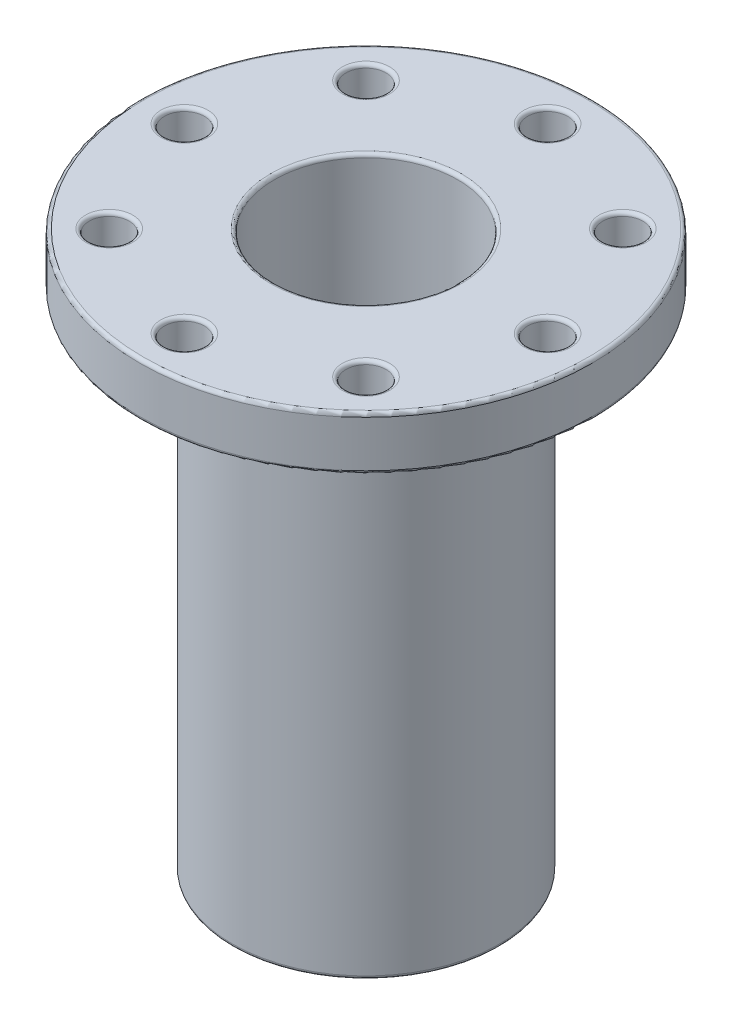
SolidWorks part; units mm, degrees
ref_plane "Front Plane" through (0, 0, 0) normal (0, 0, 1) x (1, 0, 0)
ref_plane "Top Plane" through (0, 0, 0) normal (0, 1, 0) x (1, 0, 0)
ref_plane "Right Plane" through (0, 0, 0) normal (1, 0, 0) x (0, 0, -1)
sketch "Sketch1" plane through (0, 0, 0) normal (0, 1, 0) x (1, 0, 0)
  line L0 (0, 0) -> (0, 20.4) construction
  circle A0 centre (0, 0) radius 25.4
  circle A1 centre (0, 20.4) radius 2.25
  circle A2 centre (14.425, 14.425) radius 2.25
  circle A3 centre (20.4, 0) radius 2.25
  circle A4 centre (14.425, -14.425) radius 2.25
  circle A5 centre (0, -20.4) radius 2.25
  circle A6 centre (-14.425, -14.425) radius 2.25
  circle A7 centre (-20.4, 0) radius 2.25
  circle A8 centre (-14.425, 14.425) radius 2.25
  point P22 (0, 0)
  dimension "D1" = 50.8
  dimension "D2" = 4.5
  dimension "D3" = 20.4
  dimension "D4" = 8
extrude "Boss-Extrude1" add sketch "Sketch1" along normal blind 6
sketch "Sketch2" plane through (0, 6, 0) normal (0, 1, 0) x (1, 0, 0)
  circle A0 centre (0, 0) radius 15
  dimension "D1" = 30
extrude "Boss-Extrude2" add sketch "Sketch2" against normal blind 62.5
sketch "Sketch3" plane through (0, 6, 0) normal (0, 1, 0) x (1, 0, 0)
  circle A0 centre (0, 0) radius 10.3125
  dimension "D1" = 20.625
extrude "Cut-Extrude1" cut sketch "Sketch3" against normal blind 38.1
sketch "Sketch4" plane through (0, -56.5, 0) normal (0, -1, 0) x (1, 0, 0)
  circle A0 centre (0, 0) radius 7.07
  dimension "D1" = 14.14
extrude "Cut-Extrude2" cut sketch "Sketch4" against normal through all
fillet "Fillet1" radius 0.4 24 edges at (-14.425, 6, -12.175) (-14.425, 6, 16.675) (14.425, 6, 16.675) (14.425, 6, -12.175) (0, 6, 25.4) (0, 6, -18.15) (20.4, 6, 2.25) (0, 6, 22.65) (-20.4, 6, 2.25) (-14.425, 0, -12.175) (-20.4, 0, 2.25) (-14.425, 0, 16.675) (0, 0, 22.65) (14.425, 0, 16.675) (20.4, 0, 2.25) (14.425, 0, -12.175) (0, 0, -18.15) (0, 0, 25.4) (0, 0, 15) (0, -56.5, 15) (0, -56.5, -7.07) (0, -32.1, 7.07) (0, 6, 10.3125) (0, -32.1, 10.3125)
